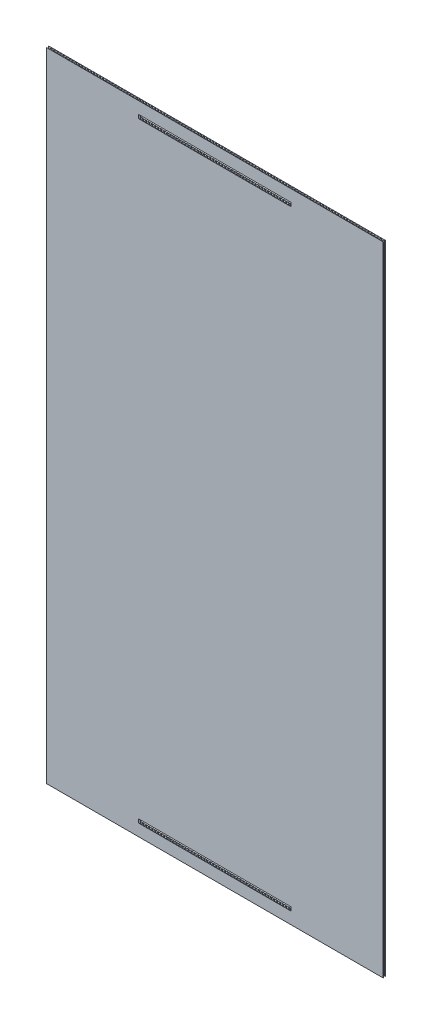
SolidWorks part; units mm, degrees
material "Acrylic (Medium-high impact)"
ref_plane "Front Plane" through (0, 0, 0) normal (0, 0, 1) x (1, 0, 0)
ref_plane "Top Plane" through (0, 0, 0) normal (0, 1, 0) x (1, 0, 0)
ref_plane "Right Plane" through (0, 0, 0) normal (1, 0, 0) x (0, 0, -1)
sketch "Sketch1" plane through (0, 0, 0) normal (0, 1, 0) x (1, 0, 0)
  line L0 (5, -4) -> (-5.3, -4)
  line L1 (-5.3, -4) -> (5, -4) construction
  line L2 (-5, -4) -> (-5, 4) construction
  line L3 (-5.3, 4) -> (5, 4) construction
  line L4 (5, -4) -> (5, 4) construction
  line L5 (-5, -4) -> (5, 4) construction
  line L6 (-5, 4) -> (5, -4) construction
  line L7 (4.7, -3.7) -> (4.7, 3.7)
  line L8 (-5.3, 3.7) -> (4.7, 3.7)
  line L9 (-5.3, -3.7) -> (4.7, -3.7)
  line L10 (5, 4) -> (5, -4)
  line L11 (-5, 4) -> (5, 4) construction
  line L12 (-5, 3.7) -> (5, 3.7) construction
  line L13 (-5, -3.7) -> (5, -3.7) construction
  line L14 (-5, -4) -> (5, -4) construction
  line L15 (5, 4) -> (-5.3, 4)
  line L16 (-5.3, 4) -> (-5.3, -4) construction
  line L17 (-5.3, 4) -> (-5.3, 3.7)
  line L18 (4.7, -4) -> (4.7, 4) construction
  line L19 (-5.3, -3.7) -> (-5.3, -4)
  point P0 (0, 0)
  dimension "D1" = 8
  dimension "D2" = 10
  dimension "D6" = 0.3
  dimension "D3" = 0.3
  dimension "D4" = 0.3
  dimension "D5" = 0.3
extrude "Boss-Extrude1" add sketch "Sketch1" along normal blind 2090
pattern_linear "LPattern1" count 111 spacing 10 along (1, 0, 0) of "Boss-Extrude1"
sketch "Sketch2" plane through (0, 0, 4) normal (0, 0, 1) x (1, 0, 0)
  line L0 (1099, 45) -> (-5.3, 45) construction
  line L2 (-5.3, 2090) -> (-5.3, 0) construction
  line L3 (-5.3, 0) -> (1105, 0) construction
  line L4 (1099, 51) -> (-5.3, 51) construction
  line L5 (1099, 38.9) -> (-5.3, 38.9) construction
  line L6 (546.85, 38.9) -> (546.85, 51) construction
  line L7 (796.95, 38.9) -> (796.95, 51)
  line L8 (296.75, 38.9) -> (296.75, 51)
  line L9 (296.75, 51) -> (796.95, 51)
  line L10 (796.95, 38.9) -> (296.75, 38.9)
  line L11 (1099, 45) -> (-5.3, 45) construction
  line L12 (1105, 0) -> (1105, 2090)
  line L13 (1099, 51) -> (-5.3, 51) construction
  line L14 (1105, 2090) -> (1099, 2090)
  line L17 (-5.3, 2090) -> (1105, 2090) construction
  line L18 (1099, 2090) -> (1099, 0)
  line L19 (-5.3, 0) -> (1105, 0) construction
  line L20 (1099, 0) -> (1105, 0)
  dimension "D1" = 45
  dimension "D6" = 6
  dimension "D2" = 6
  dimension "D3" = 12.1
  dimension "D4" = 250.1
  dimension "D5" = 250.1
extrude "Cut-Extrude1" cut sketch "Sketch2" against normal through all
pattern_linear "LPattern2" count 2 spacing 2000 along (0, 1, 0) of "Cut-Extrude1"
